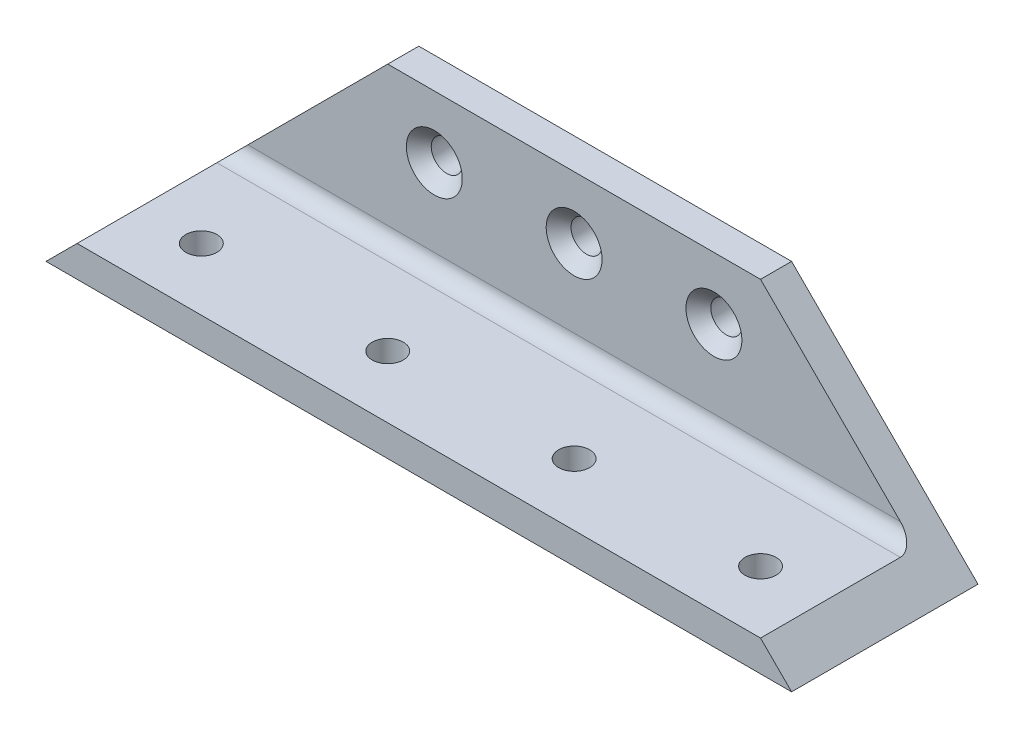
SolidWorks part; units mm, degrees
material "6061-T6 (SS)"
ref_plane "Front Plane" through (0, 0, 0) normal (0, 0, 1) x (1, 0, 0)
ref_plane "Top Plane" through (0, 0, 0) normal (0, 1, 0) x (1, 0, 0)
ref_plane "Right Plane" through (0, 0, 0) normal (1, 0, 0) x (0, 0, -1)
sketch "Sketch1" plane through (0, 0, 0) normal (1, 0, 0) x (0, 0, -1)
  line L1 (19.05, -19.05) -> (-19.05, -19.05)
  line L2 (19.05, -19.05) -> (19.05, 19.05)
  line L3 (19.05, 19.05) -> (12.7, 19.05)
  line L4 (-19.05, -19.05) -> (-19.05, -12.7)
  line L7 (12.7, -12.7) -> (-19.05, -12.7)
  line L8 (12.7, -12.7) -> (12.7, 19.05)
  point P0 (0, 0)
  point P6 (-6.9563, 6.9563)
  dimension "D1" = 38.1
  dimension "D2" = 38.1
  dimension "D3" = 6.35
  dimension "D4" = 6.35
extrude "Boss-Extrude1" add sketch "Sketch1" along normal blind 152.4
fillet "Fillet1" radius 3.175 1 edges at (76.2, -12.7, -12.7)
sketch "Sketch2" plane through (0, 0, -19.05) normal (0, 0, -1) x (-1, 0, 0)
  line L0 (-152.4, -19.05) -> (-152.4, 19.05) construction
  line L1 (-152.4, -19.05) -> (0, -19.05) construction
  circle A0 centre (-104.775, 6.35) radius 3.175
  circle A1 centre (-76.2, 6.35) radius 3.175
  circle A2 centre (-47.625, 6.35) radius 3.175
  dimension "D7" = 6.35
  dimension "D8" = 6.35
  dimension "D9" = 6.35
  dimension "D1" = 47.625
  dimension "D2" = 76.2
  dimension "D3" = 104.775
  dimension "D4" = 25.4
  dimension "D5" = 25.4
  dimension "D6" = 25.4
extrude "Cut-Extrude2" cut sketch "Sketch2" against normal blind 152.4
chamfer "Chamfer1" distance 2.54 angle 45 1 edges at (44.45, 6.35, -12.7)
chamfer "Chamfer2" distance 2.54 angle 45 2 edges at (101.6, 6.35, -12.7) (73.025, 6.35, -12.7)
sketch "Sketch3" plane through (0, -12.7, 0) normal (0, 1, 0) x (1, 0, 0)
  line L0 (152.4, -19.05) -> (0, -19.05) construction
  line L1 (0, 9.525) -> (0, -19.05) construction
  line L2 (152.4, 9.525) -> (152.4, -19.05) construction
  circle A0 centre (19.05, -6.35) radius 3.175
  circle A1 centre (57.15, -6.35) radius 3.175
  circle A2 centre (95.25, -6.35) radius 3.175
  circle A3 centre (133.35, -6.35) radius 3.175
  dimension "D9" = 6.35
  dimension "D10" = 6.35
  dimension "D11" = 6.35
  dimension "D12" = 6.35
  dimension "D1" = 12.7
  dimension "D2" = 12.7
  dimension "D3" = 12.7
  dimension "D4" = 12.7
  dimension "D5" = 19.05
  dimension "D6" = 19.05
  dimension "D7" = 57.15
  dimension "D8" = 57.15
extrude "Cut-Extrude3" cut sketch "Sketch3" against normal blind 152.4
sketch "Sketch4" plane through (0, 0, -19.05) normal (0, 0, -1) x (-1, 0, 0)
  line L0 (-152.4, -19.05) -> (-114.3, 19.05)
  line L1 (-152.4, 19.05) -> (0, 19.05) construction
  line L2 (0, -19.05) -> (-38.1, 19.05)
  line L3 (-152.4, -19.05) -> (-152.4, 19.05) construction
  line L4 (0, -19.05) -> (0, 19.05) construction
  line L5 (-114.3, 19.05) -> (-152.4, 19.05)
  line L6 (-152.4, 19.05) -> (-152.4, -19.05)
  line L7 (-38.1, 19.05) -> (0, 19.05)
  line L8 (0, 19.05) -> (0, -19.05)
  dimension "D1" = 38.1
  dimension "D2" = 38.1
extrude "Cut-Extrude4" cut sketch "Sketch4" against normal blind 152.4
